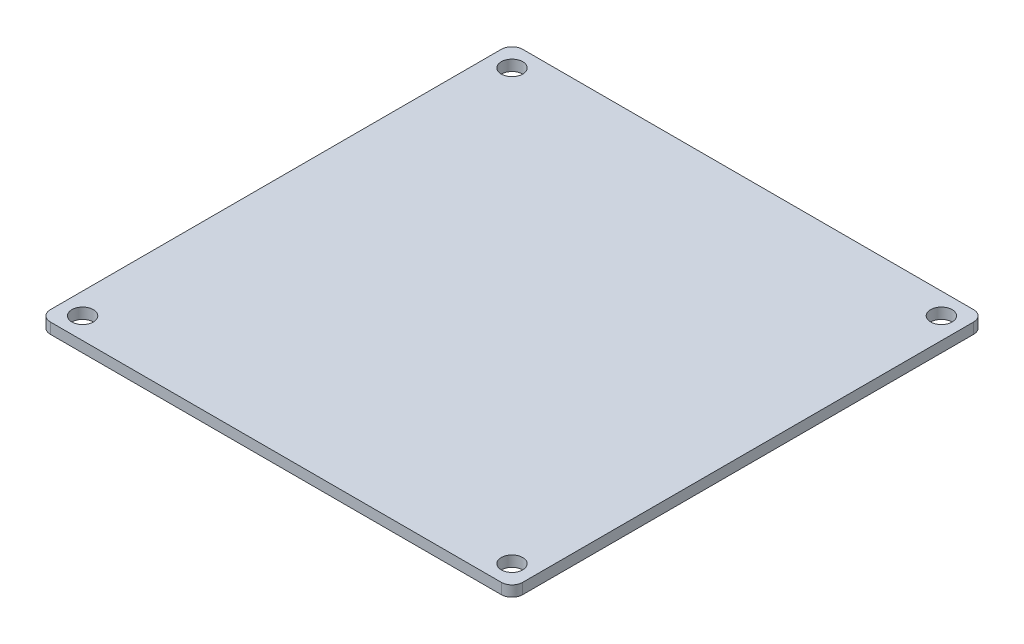
SolidWorks part; units mm, degrees
ref_plane "Спереди" through (0, 0, 0) normal (0, 0, 1) x (1, 0, 0)
ref_plane "Сверху" through (0, 0, 0) normal (0, 1, 0) x (1, 0, 0)
ref_plane "Справа" through (0, 0, 0) normal (1, 0, 0) x (0, 0, -1)
sketch "Эскиз1" plane through (0, 0, 0) normal (0, 1, 0) x (1, 0, 0)
  line L1 (-31.5, 33) -> (31.5, 33)
  line L2 (-33, 31.5) -> (-33, -31.5)
  line L3 (-31.5, -33) -> (31.5, -33)
  line L4 (33, 31.5) -> (33, -31.5)
  line L5 (-33, 33) -> (33, -33) construction
  line L6 (-33, -33) -> (33, 33) construction
  line L7 (-30, 30) -> (30, 30) construction
  line L8 (-30, 30) -> (-30, -30) construction
  line L9 (-30, -30) -> (30, -30) construction
  line L10 (30, 30) -> (30, -30) construction
  line L11 (-30, 30) -> (30, -30) construction
  line L12 (-30, -30) -> (30, 30) construction
  circle A0 centre (-30, 30) radius 1.5
  circle A1 centre (30, 30) radius 1.5
  circle A2 centre (30, -30) radius 1.5
  circle A3 centre (-30, -30) radius 1.5
  arc A4 (-33, -31.5) -> (-31.5, -33) centre (-31.5, -31.5) ccw
  arc A5 (31.5, -33) -> (33, -31.5) centre (31.5, -31.5) ccw
  arc A6 (31.5, 33) -> (33, 31.5) centre (31.5, 31.5) cw
  arc A7 (-31.5, 33) -> (-33, 31.5) centre (-31.5, 31.5) ccw
  point P0 (0, 0)
  point P6 (0, 0)
  point P27 (0, 0)
  point P30 (-7.7608, 18.9674)
  point P32 (0, 0)
  point P33 (8.0604, 27.1177)
  point P36 (-22.5, 22.5)
  point P37 (-22.5, 22.5)
  dimension "D5" = 3
  dimension "D6" = 3
  dimension "D7" = 3
  dimension "D8" = 3
  dimension "D9" = 1.5
  dimension "D1" = 66
  dimension "D2" = 66
  dimension "D3" = 60
  dimension "D4" = 60
extrude "Бобышка-Вытянуть1" add sketch "Эскиз1" along normal blind 1.5
